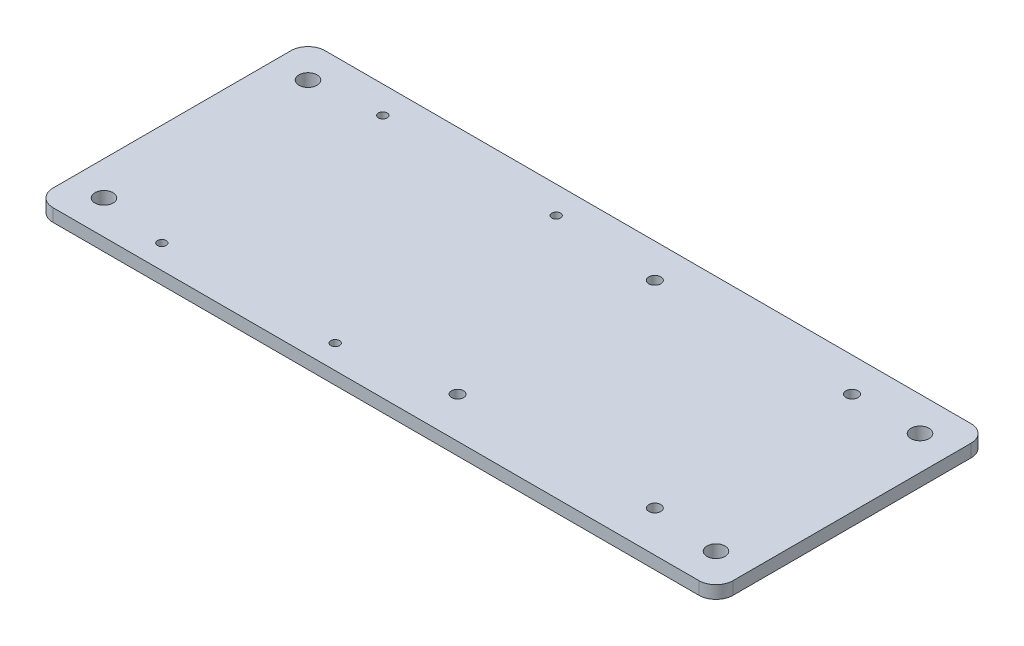
SolidWorks part; units mm, degrees
ref_plane "Front Plane" through (0, 0, 0) normal (0, 0, 1) x (1, 0, 0)
ref_plane "Top Plane" through (0, 0, 0) normal (0, 1, 0) x (1, 0, 0)
ref_plane "Right Plane" through (0, 0, 0) normal (1, 0, 0) x (0, 0, -1)
sketch "Sketch2" plane through (0, 0, 0) normal (0, 1, 0) x (1, 0, 0)
  line L1 (0, 0) -> (254, 0)
  line L2 (0, 0) -> (0, -101.6)
  line L3 (0, -101.6) -> (254, -101.6)
  line L4 (254, 0) -> (254, -101.6)
  point P7 (12.7, -88.9)
  point P8 (12.7, -12.7)
  point P9 (241.3, -88.9)
  point P10 (241.3, -12.7)
  point P11 (0, 0)
  point P12 (0, 0)
  point P13 (0, 0)
  point P14 (0, 0)
  point P15 (0, 0)
  dimension "D1" = 101.6
  dimension "D2" = 254
  dimension "D6" = 12.7
  dimension "D7" = 12.7
  dimension "D8" = 12.7
  dimension "D9" = 12.7
extrude "Boss-Extrude1" add sketch "Sketch2" along normal blind 4.7625
fillet "Fillet1" radius 6.35 4 edges at (254, 2.3813, 0) (254, 2.3813, 101.6) (0, 2.3813, 101.6) (0, 2.3813, 0)
hole_wizard "1/4 Clearance Hole1" positions "Sketch5" profile "Sketch6" hole size "1/4" standard "ANSI Inch" end condition through all
sketch "Sketch5" plane through (0, 4.7625, 0) normal (0, 1, 0) x (1, 0, 0)
  point P0 (12.7, -12.7)
  point P3 (12.7, -88.9)
  point P6 (241.3, -88.9)
  point P9 (241.3, -12.7)
sketch "Sketch6" plane through (12.7, 4.7625, 12.7) normal (1, 0, 0) x (0, 0, 1)
  line L0 (0, 0) -> (0, 4.7625)
  line L1 (0, 4.7625) -> (3.3782, 4.7625)
  line L2 (3.3782, 4.7625) -> (3.3782, 0)
  line L5 (3.3782, 0) -> (0, 0)
  line L11 (0, -6.35) -> (0, 107.95) construction
  dimension "Thru Hole Dia." = 6.7564
  dimension "Thru Hole Depth" = 4.7625
sketch "Sketch7" plane through (0, 4.7625, 0) normal (0, 1, 0) x (1, 0, 0)
  point P0 (142.24, -12.7)
  point P1 (215.9, -12.7)
  point P2 (142.24, -86.36)
  point P3 (215.9, -86.36)
  point P4 (0, 0)
  point P5 (0, 0)
  point P6 (0, 0)
  point P7 (0, 0)
  point P8 (228.044, -12.7)
  dimension "D1" = 73.66
  dimension "D2" = 73.66
  dimension "D3" = 25.4
hole_wizard "#8 Clearance Hole1" positions "Sketch8" profile "Sketch9" hole size "#8" standard "ANSI Inch" end condition through all
sketch "Sketch8" plane through (0, 4.7625, 0) normal (0, 1, 0) x (1, 0, 0)
  point P0 (142.24, -12.7)
  point P3 (215.9, -12.7)
  point P6 (215.9, -86.36)
  point P9 (142.24, -86.36)
sketch "Sketch9" plane through (142.24, 4.7625, 12.7) normal (1, 0, 0) x (0, 0, 1)
  line L0 (0, 0) -> (0, 4.7625)
  line L1 (0, 4.7625) -> (2.2479, 4.7625)
  line L2 (2.2479, 4.7625) -> (2.2479, 0)
  line L5 (2.2479, 0) -> (0, 0)
  line L11 (0, -6.35) -> (0, 107.95) construction
  dimension "Thru Hole Dia." = 4.4958
  dimension "Thru Hole Depth" = 4.7625
sketch "Sketch10" plane through (0, 4.7625, 0) normal (0, 1, 0) x (1, 0, 0)
  line L0 (0, 0) -> (254, 0) construction
  point P0 (38.1, -10.16)
  point P1 (38.1, -92.71)
  point P2 (102.87, -92.71)
  point P3 (102.87, -10.16)
  point P4 (0, 0)
  point P5 (0, 0)
  point P6 (0, 0)
  point P7 (0, 0)
  point P9 (0, 0)
  dimension "D1" = 82.55
  dimension "D2" = 64.77
  dimension "D3" = 25.4
  dimension "D4" = 10.16
hole_wizard "#4 Clearance Hole1" positions "Sketch11" profile "Sketch12" hole size "#4" standard "ANSI Inch" end condition through all
sketch "Sketch11" plane through (0, 4.7625, 0) normal (0, 1, 0) x (1, 0, 0)
  point P0 (38.1, -10.16)
  point P3 (102.87, -10.16)
  point P6 (102.87, -92.71)
  point P9 (38.1, -92.71)
sketch "Sketch12" plane through (38.1, 4.7625, 10.16) normal (1, 0, 0) x (0, 0, 1)
  line L0 (0, 0) -> (0, 4.7625)
  line L1 (0, 4.7625) -> (1.6319, 4.7625)
  line L2 (1.6319, 4.7625) -> (1.6319, 0)
  line L5 (1.6319, 0) -> (0, 0)
  line L11 (0, -6.35) -> (0, 107.95) construction
  dimension "Thru Hole Dia." = 3.2639
  dimension "Thru Hole Depth" = 4.7625
